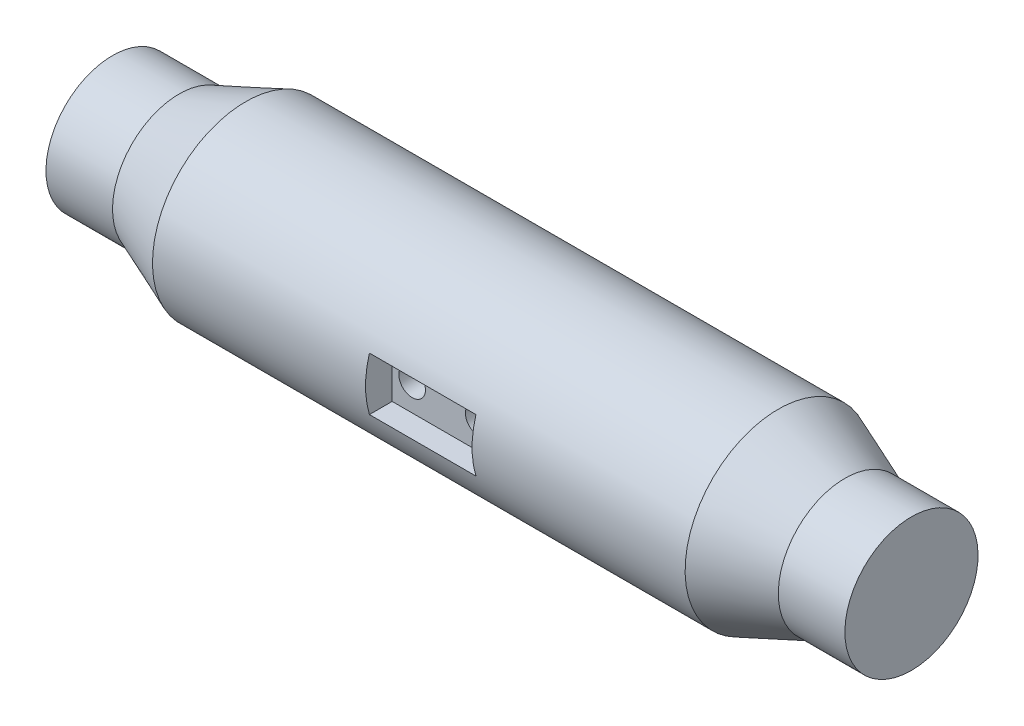
SolidWorks part; units mm, degrees
ref_plane "Plan de face" through (0, 0, 0) normal (0, 0, 1) x (1, 0, 0)
ref_plane "Plan de dessus" through (0, 0, 0) normal (0, 1, 0) x (1, 0, 0)
ref_plane "Plan de droite" through (0, 0, 0) normal (1, 0, 0) x (0, 0, -1)
sketch "Esquisse1" plane through (0, 0, 0) normal (0, 0, 1) x (1, 0, 0)
  line L0 (-30, 0) -> (30, 0)
  line L1 (30, 0) -> (30, 5)
  line L2 (30, 5) -> (25, 5)
  line L3 (25, 5) -> (20, 7)
  line L4 (20, 7) -> (-20, 7)
  line L6 (-25, 5) -> (-20, 7)
  line L7 (-30, 5) -> (-25, 5)
  line L8 (-30, 0) -> (-30, 5)
  dimension "D2" = 5
  dimension "D3" = 5
revolve "Révolution1" add sketch "Esquisse1" angle 360 about L0
ref_plane "Plan1" through (0, 0, 7) normal (0, 0, 1) x (1, 0, 0)
sketch "Esquisse2" plane through (0, 0, 7) normal (0, 0, 1) x (1, 0, 0)
  line L1 (-4, -2) -> (4, -2)
  line L2 (-4, -2) -> (-4, 2)
  line L3 (-4, 2) -> (4, 2)
  line L4 (4, -2) -> (4, 2)
  line L5 (-4, -2) -> (4, 2) construction
  line L6 (-4, 2) -> (4, -2) construction
  point P0 (0, 0)
  dimension "D1" = 8
  dimension "D2" = 4
extrude "Enlèv. mat.-Extru.2" cut sketch "Esquisse2" against normal blind 2
sketch "Esquisse3" plane through (0, 0, 5) normal (0, 0, 1) x (1, 0, 0)
  circle A0 centre (2.5, 0) radius 1
  circle A1 centre (-2.5, 0) radius 1
  point P8 (0, 0)
  dimension "D1" = 2.5
  dimension "D2" = 2
  dimension "D3" = 2
extrude "Enlèv. mat.-Extru.3" cut sketch "Esquisse3" against normal blind 10
